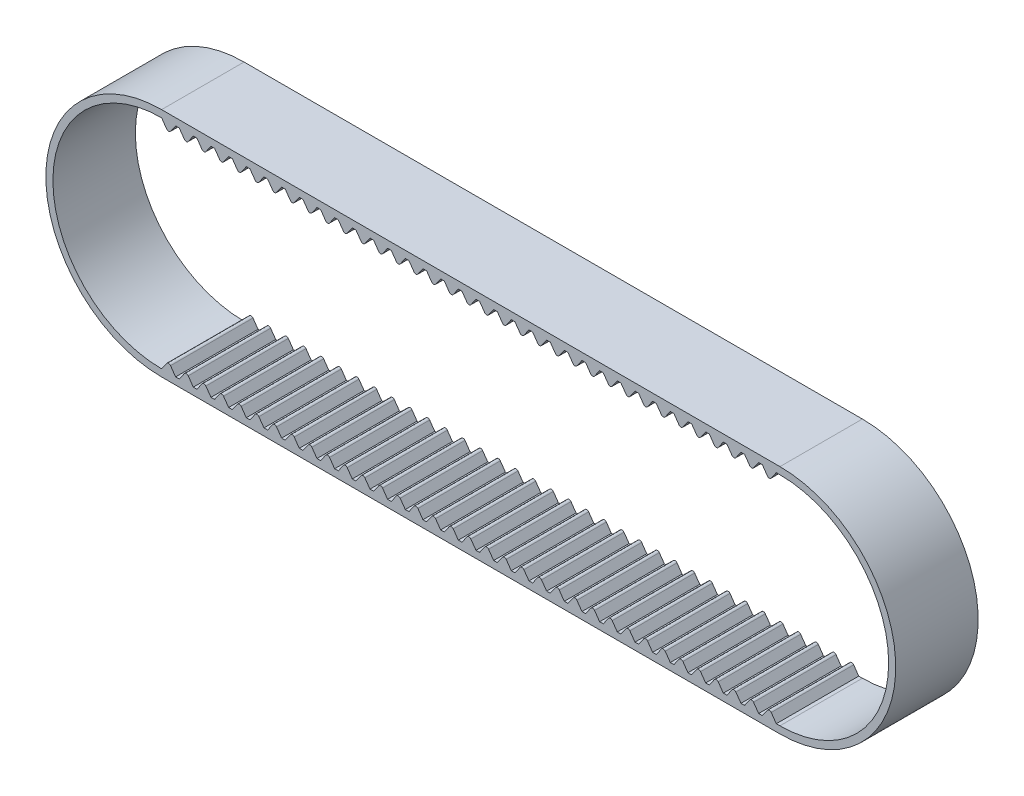
SolidWorks part; units mm, degrees
material "NEOPREN"
ref_plane "Ebene vorne" through (0, 0, 0) normal (0, 0, 1) x (1, 0, 0)
ref_plane "Ebene oben" through (0, 0, 0) normal (0, 1, 0) x (1, 0, 0)
ref_plane "Ebene rechts" through (0, 0, 0) normal (1, 0, 0) x (0, 0, -1)
sketch "Skizze1" plane through (0, 0, 0) normal (0, 0, 1) x (1, 0, 0)
  line L0 (26.25, 0) -> (-26.25, 0) construction
  line L1 (26.25, -9.83) -> (-26.25, -9.83)
  line L2 (26.25, 9.83) -> (-26.25, 9.83)
  arc A0 (26.25, -9.83) -> (26.25, 9.83) centre (26.25, 0) ccw
  arc A1 (-26.25, 9.83) -> (-26.25, -9.83) centre (-26.25, 0) ccw
  circle A2 centre (-26.25, 0) radius 9.83 construction
  circle A3 centre (26.25, 0) radius 9.83 construction
  point P2 (0, 0)
  point P12 (-16.42, 0)
  point P13 (16.42, 0)
  dimension "D1" = 52.5
  dimension "D2" = 19.66
  dimension "D3" = 32.84
extrude "Linear-Austragen-Dünn1" add sketch "Skizze1" along normal mid plane 7 thin
sketch "Skizze2" plane through (0, 0, 3.5) normal (0, 0, 1) x (1, 0, 0)
  line L0 (-26.25, 9.23) -> (-25.8187, 8.6152)
  line L1 (-25.4913, 8.6152) -> (-25.06, 9.23)
  line L2 (26.25, 9.23) -> (-26.25, 9.23) construction
  line L3 (-25.06, 9.23) -> (-26.25, 9.23)
  line L4 (-25.655, 9.23) -> (-25.655, 8.3817) construction
  arc A0 (-25.8187, 8.6152) -> (-25.4913, 8.6152) centre (-25.655, 8.73) ccw
  point P10 (-25.655, 8.53)
  dimension "D2" = 0.2
  dimension "D1" = 1.19
  dimension "D3" = 0.7
extrude "Aufsatz-Linear austragen1" add sketch "Skizze2" against normal up to surface (7 mm away) up to face at (0, 0, -3.5)
pattern_linear "Lineares Muster1" count 35 spacing 1.5 along (1, 0, 0) of "Aufsatz-Linear austragen1"
mirror "Spiegeln1" about plane through (0, 0, 0) normal (0, 1, 0) of "Lineares Muster1", "Aufsatz-Linear austragen1"
